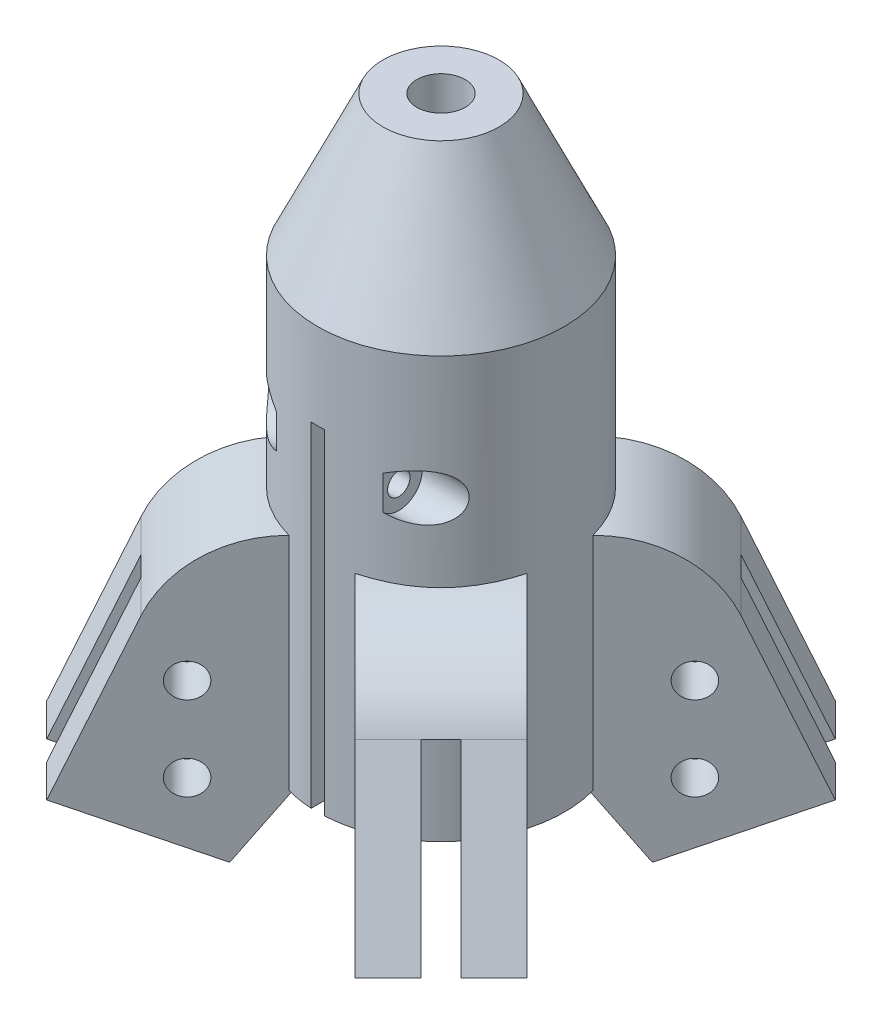
SolidWorks part; units mm, degrees
ref_plane "Front Plane" through (0, 0, 0) normal (0, 0, 1) x (1, 0, 0)
ref_plane "Top Plane" through (0, 0, 0) normal (0, 1, 0) x (1, 0, 0)
ref_plane "Right Plane" through (0, 0, 0) normal (1, 0, 0) x (0, 0, -1)
sketch "Sketch1" plane through (0, 0, 0) normal (0, 1, 0) x (1, 0, 0)
  circle A1 centre (0, 0) radius 13.21
  circle A4 centre (0, 0) radius 2.585
  circle A5 centre (0, 0) radius 2.585
  dimension "D1" = 0.5
  dimension "D2" = 13.21
extrude "Boss-Extrude1" add sketch "Sketch1" along normal blind 20
ref_plane "Plane1" through (0, 0, 0) normal (0.7071, 0, 0.7071) x (0, -1, 0)
chamfer "Chamfer1" distance 1.2 angle 45 1 edges at (0, 0, 2.585)
sketch "Sketch7" plane through (0, 0, 0) normal (0, -1, 0) x (1, 0, 0)
  circle A2 centre (0, 0) radius 13.21 construction
  circle A3 centre (0, 0) radius 13.21
  circle A4 centre (0, 0) radius 3.785 construction
  circle A5 centre (0, 0) radius 3.785
extrude "Boss-Extrude5" add sketch "Sketch7" along normal blind 40
sketch "Sketch8" plane through (0, 0, 0) normal (1, 0, 0) x (0, 0, -1)
  line L0 (-11.21, -4.2) -> (-3.1708, -4.2) construction
  line L1 (-13.21, -4.2) -> (0, -4.2)
  line L2 (-13.21, -4.2) -> (-13.21, -40)
  line L3 (-13.21, -40) -> (0, -40)
  line L4 (0, -4.2) -> (0, -40)
extrude "Cut-Extrude3" cut sketch "Sketch8" along normal offset from surface 0.2 and the other way offset from surface (0.7 mm away) 0.2
sketch "Sketch11" plane through (0, 0, 0) normal (1, 0, 0) x (0, 0, -1)
  line L0 (-3.7197, -4.2) -> (-13.1914, -4.2) construction
  line L1 (0, -4.2) -> (13.21, -4.2)
  line L2 (0, -4.2) -> (0, -40)
  line L3 (0, -40) -> (13.21, -40)
  line L4 (13.21, -4.2) -> (13.21, -40)
  line L5 (-13.1914, -40) -> (13.21, -40) construction
  line L6 (13.21, -40) -> (13.21, 20) construction
extrude "Cut-Extrude5" cut sketch "Sketch11" against normal mid plane 5
sketch "Sketch12" plane through (0.7, 0, 0) normal (-1, 0, 0) x (0, 0, 1)
  circle A0 centre (10.21, -8.2) radius 1.2 construction
  circle A1 centre (10.21, -8.2) radius 1.2
extrude "Cut-Extrude6" cut sketch "Sketch12" against normal through all both and the other way through all
ref_plane "Plane2" through (5.7, 0, 0) normal (-1, 0, 0) x (0, 0, 1)
sketch "Sketch13" plane through (5.7, 0, 0) normal (-1, 0, 0) x (0, 0, 1)
  circle A0 centre (10.21, -8.2) radius 2.5
  circle A1 centre (10.21, -8.2) radius 1.2 construction
  dimension "D1" = 5
extrude "Cut-Extrude7" cut sketch "Sketch13" against normal through all
mirror "Mirror2" about plane through (0, 0, 0) normal (1, 0, 0) of "Cut-Extrude7"
sketch "Sketch15" plane through (-1.0607, 0, -1.0607) normal (-0.7071, 0, -0.7071) x (-0.7071, 0, 0.7071)
  line L0 (-22.7042, -23.8102) -> (-11.21, -23.8102)
  line L3 (-22.7042, -23.8102) -> (-59.1395, -111.0537) construction
  line L7 (-22.7042, -23.8102) -> (-29.8316, -40.8765)
  line L8 (-11.21, -35.211) -> (-11.21, -23.8102)
  line L10 (-15.9902, -46.6571) -> (-29.8316, -40.8765)
  line L11 (-13.21, -40) -> (-11.21, -40) construction
  line L12 (-11.21, -40) -> (-11.21, -35.211)
  line L13 (-3.7773, -40) -> (-10.9398, -40) construction
  line L14 (-15.9902, -46.6571) -> (-11.21, -40)
  line L16 (-30, -80.2034) -> (-13.21, -40) construction
  circle A0 centre (-19.21, -29.8102) radius 1.8 construction
  circle A1 centre (-19.21, -38.8102) radius 1.8 construction
  circle A2 centre (-19.21, -29.8102) radius 1.8
  circle A3 centre (-19.21, -38.8102) radius 1.8
  dimension "D1" = 2
  dimension "D2" = 6
extrude "Boss-Extrude6" add sketch "Sketch15" along normal blind 5
ref_plane "Plane3" through (0, 0, 0) normal (0.7071, 0, 0.7071) x (0.7071, 0, -0.7071)
mirror "Mirror3" about plane through (0, 0, 0) normal (0.7071, 0, 0.7071) of "Boss-Extrude6"
sketch "Sketch16" plane through (-4.5962, 0, -4.5962) normal (-0.7071, 0, -0.7071) x (-0.7071, 0, 0.7071)
  line L0 (-22.7042, -23.8102) -> (-29.8316, -40.8765) construction
  line L1 (-22.7042, -23.8102) -> (-29.8316, -40.8765) construction
  line L2 (-11.5002, -23.8102) -> (-11.5002, -40) construction
  line L3 (-11.5002, -23.8102) -> (-11.5002, -40) construction
  line L4 (-11.5002, -23.8102) -> (-22.7042, -23.8102) construction
  line L5 (-11.5002, -23.8102) -> (-22.7042, -23.8102)
  line L6 (-11.5002, -23.8102) -> (-11.5002, -16.3474)
  arc A0 (-22.7042, -23.8102) -> (-11.5002, -16.3474) centre (-11.5002, -28.4893) cw
extrude "Boss-Extrude7" add sketch "Sketch16" against normal up to surface (13 mm away) up to face at (16.9069, -38.8102, -7.7145)
pattern_circular "CirPattern2" count 4 over 360 about axis through (0, 0, 0) along (0, 1, 0) of "Boss-Extrude7", "Mirror3", "Boss-Extrude6"
chamfer "Chamfer2" distance 15 angle 25 1 edges at (0, 20, 13.21)
